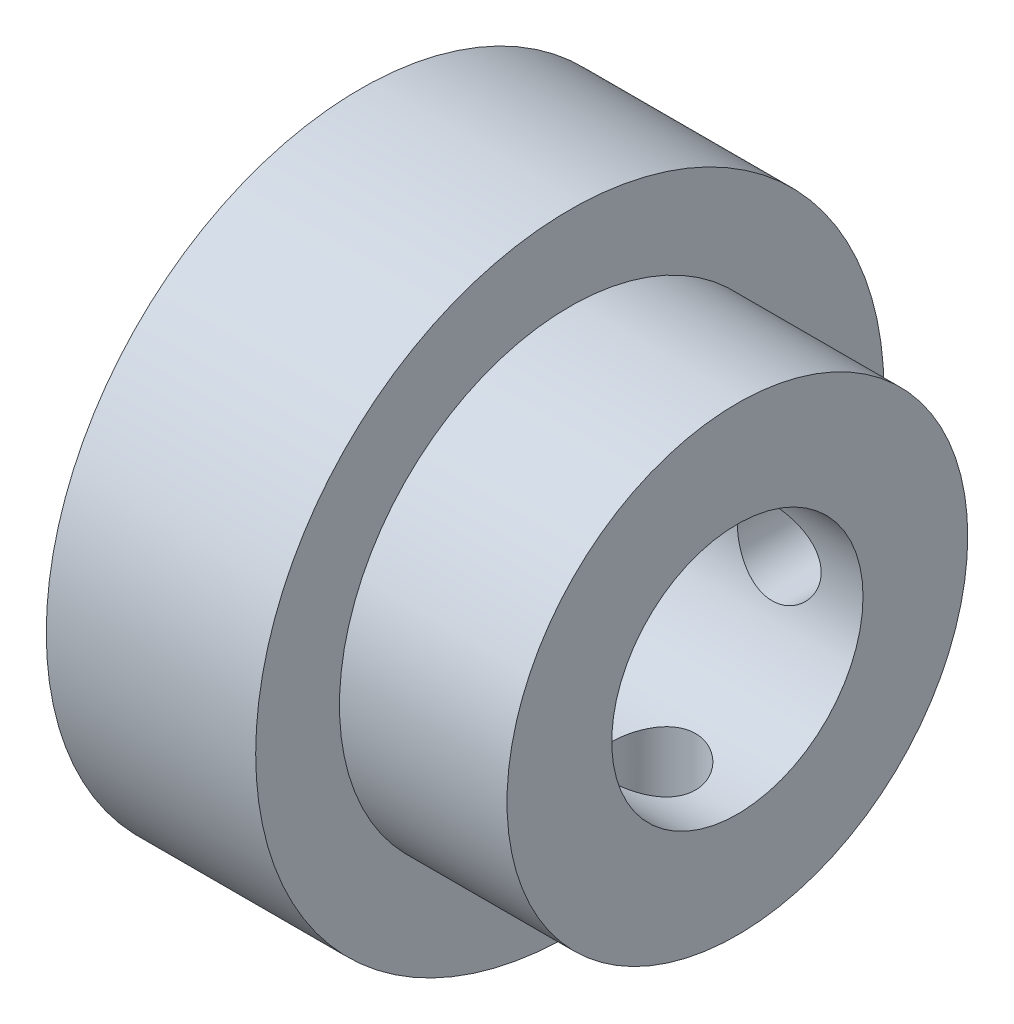
SolidWorks part; units mm, degrees
ref_plane "Piano frontale" through (0, 0, 0) normal (0, 0, 1) x (1, 0, 0)
ref_plane "Piano superiore" through (0, 0, 0) normal (0, 1, 0) x (1, 0, 0)
ref_plane "Piano destro" through (0, 0, 0) normal (1, 0, 0) x (0, 0, -1)
ref_axis "Assi1" through (88.99, 0, 0) along (-1, 0, 0)
sketch "Schizzo1" plane through (0, 0, 0) normal (0, 0, 1) x (1, 0, 0)
  line L0 (-25.1755, 6) -> (-25.1755, 15)
  line L1 (-25.1755, 15) -> (-15.1755, 15)
  line L2 (-15.1755, 15) -> (-15.1755, 11)
  line L3 (-15.1755, 11) -> (-7.1755, 11)
  line L4 (-7.1755, 11) -> (-7.1755, 6)
  line L5 (-7.1755, 6) -> (-25.1755, 6)
  line L6 (88.99, 0) -> (-88.99, 0) construction
  point P8 (-20.1755, 15)
  dimension "D1" = 6
  dimension "D2" = 11
  dimension "D3" = 15
  dimension "D4" = 8
  dimension "D5" = 18
revolve "Rivoluzione1" add sketch "Schizzo1" angle 360 about axis through (88.99, 0, 0) along (-1, 0, 0)
sketch "Schizzo2" plane through (0, 0, 0) normal (0, 0, 1) x (1, 0, 0)
  line L0 (-7.1755, -6) -> (-7.1755, 6) construction
  line L1 (88.99, 0) -> (-88.99, 0) construction
  circle A0 centre (-11.1755, 0) radius 2
  point P4 (0, 0)
  dimension "D2" = 4
  dimension "D1" = 4
extrude "Taglio-Estrusione1" cut sketch "Schizzo2" against normal through all
sketch "Schizzo3" plane through (0, 0, 0) normal (0, 1, 0) x (1, 0, 0)
  line L1 (-7.1755, -6) -> (-7.1755, 6) construction
  line L2 (88.99, 0) -> (-88.99, 0) construction
  circle A0 centre (-11.1755, 0) radius 2
  point P4 (-12.5711, -23.1578)
  point P5 (0, 0)
  dimension "D1" = 4
  dimension "D2" = 4
extrude "Taglio-Estrusione2" cut sketch "Schizzo3" against normal through all
